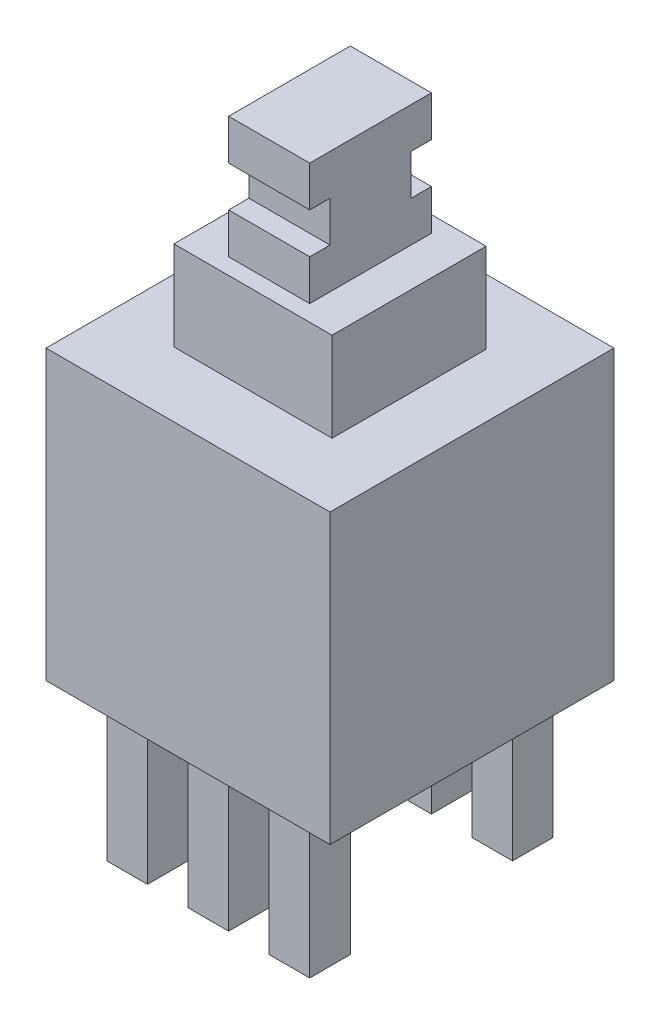
SolidWorks part; units mm, degrees
ref_plane "Front Plane" through (0, 0, 0) normal (0, 0, 1) x (1, 0, 0)
ref_plane "Top Plane" through (0, 0, 0) normal (0, 1, 0) x (1, 0, 0)
ref_plane "Right Plane" through (0, 0, 0) normal (1, 0, 0) x (0, 0, -1)
sketch "Sketch1" plane through (0, 0, 0) normal (0, 1, 0) x (1, 0, 0)
  line L1 (-3.5, -3.5) -> (3.5, -3.5)
  line L2 (-3.5, -3.5) -> (-3.5, 3.5)
  line L3 (-3.5, 3.5) -> (3.5, 3.5)
  line L4 (3.5, -3.5) -> (3.5, 3.5)
  line L5 (-3.5, -3.5) -> (3.5, 3.5) construction
  line L6 (-3.5, 3.5) -> (3.5, -3.5) construction
  point P0 (0, 0)
  dimension "D1" = 7
extrude "Boss-Extrude1" add sketch "Sketch1" along normal blind 7.1
sketch "Sketch2" plane through (0, 7.1, 0) normal (0, 1, 0) x (1, 0, 0)
  line L1 (-1.95, -1.9) -> (1.95, -1.9)
  line L2 (-1.95, -1.9) -> (-1.95, 1.9)
  line L3 (-1.95, 1.9) -> (1.95, 1.9)
  line L4 (1.95, -1.9) -> (1.95, 1.9)
  line L5 (-1.95, -1.9) -> (1.95, 1.9) construction
  line L6 (-1.95, 1.9) -> (1.95, -1.9) construction
  point P0 (0, 0)
  dimension "D1" = 3.9
  dimension "D2" = 3.8
extrude "Boss-Extrude2" add sketch "Sketch2" along normal blind 2.2
sketch "Sketch3" plane through (0, 9.3, 0) normal (0, 1, 0) x (1, 0, 0)
  line L1 (-1, -1.5) -> (1, -1.5)
  line L2 (-1, -1.5) -> (-1, 1.5)
  line L3 (-1, 1.5) -> (1, 1.5)
  line L4 (1, -1.5) -> (1, 1.5)
  line L5 (-1, -1.5) -> (1, 1.5) construction
  line L6 (-1, 1.5) -> (1, -1.5) construction
  point P0 (0, 0)
  dimension "D1" = 2
  dimension "D2" = 3
extrude "Boss-Extrude3" add sketch "Sketch3" along normal blind 3
sketch "Sketch4" plane through (0, 0, 0) normal (0, -1, 0) x (1, 0, 0)
  line L0 (-0.5, 3) -> (-0.5, 2)
  line L1 (-2.5, 3) -> (-1.5, 3)
  line L2 (-2.5, 3) -> (-2.5, 2)
  line L3 (-2.5, 2) -> (-1.5, 2)
  line L4 (-1.5, 3) -> (-1.5, 2)
  line L5 (-0.5, 3) -> (0.5, 3)
  line L6 (0.5, 3) -> (0.5, 2)
  line L7 (-0.5, 2) -> (0.5, 2)
  line L8 (1.5, 3) -> (1.5, 2)
  line L9 (1.5, 3) -> (2.5, 3)
  line L10 (2.5, 3) -> (2.5, 2)
  line L11 (1.5, 2) -> (2.5, 2)
  line L12 (-0.5, -2) -> (-0.5, -3)
  line L13 (-0.5, -2) -> (0.5, -2)
  line L14 (0.5, -2) -> (0.5, -3)
  line L15 (-0.5, -3) -> (0.5, -3)
  line L16 (1.5, -2) -> (1.5, -3)
  line L17 (1.5, -2) -> (2.5, -2)
  line L18 (2.5, -2) -> (2.5, -3)
  line L19 (1.5, -3) -> (2.5, -3)
  line L20 (-2.5, -2) -> (-2.5, -3)
  line L21 (-2.5, -2) -> (-1.5, -2)
  line L22 (-1.5, -2) -> (-1.5, -3)
  line L23 (-2.5, -3) -> (-1.5, -3)
  point P4 (-2, 2)
  point P6 (-2.5, 2.5)
  point P7 (2.5, -2.5)
  point P8 (2, -2)
  point P29 (2, 2)
  dimension "D1" = 2
  dimension "D2" = 1
  dimension "D3" = 1
  dimension "D4" = 2.5
  dimension "D7" = 2.5
  dimension "D8" = 2
  dimension "D9" = 2
  dimension "D5" = 3
  dimension "D6" = 2
extrude "Boss-Extrude4" add sketch "Sketch4" along normal blind 3.6
sketch "Sketch5" plane through (1, 0, 0) normal (1, 0, 0) x (0, 0, -1)
  line L0 (-1.5, 12.3) -> (-1.5, 9.3) construction
  line L1 (-1.5, 11.3) -> (-1, 11.3)
  line L2 (-1.5, 11.3) -> (-1.5, 10.3)
  line L3 (-1.5, 10.3) -> (-1, 10.3)
  line L4 (-1, 11.3) -> (-1, 10.3)
  line L5 (1.5, 12.3) -> (1.5, 9.3) construction
  line L6 (1.5, 11.3) -> (1, 11.3)
  line L7 (1.5, 11.3) -> (1.5, 10.3)
  line L8 (1.5, 10.3) -> (1, 10.3)
  line L9 (1, 11.3) -> (1, 10.3)
  line L10 (-1.5, 12.3) -> (1.5, 12.3) construction
  dimension "D1" = 0.5
  dimension "D2" = 1
  dimension "D3" = 1
extrude "Cut-Extrude1" cut sketch "Sketch5" against normal through all
equation "\"D7@Sketch4\"=\"D4@Sketch4\""
equation "\"D8@Sketch4\"=\"D1@Sketch4\""
equation "\"D9@Sketch4\"=\"D1@Sketch4\""
